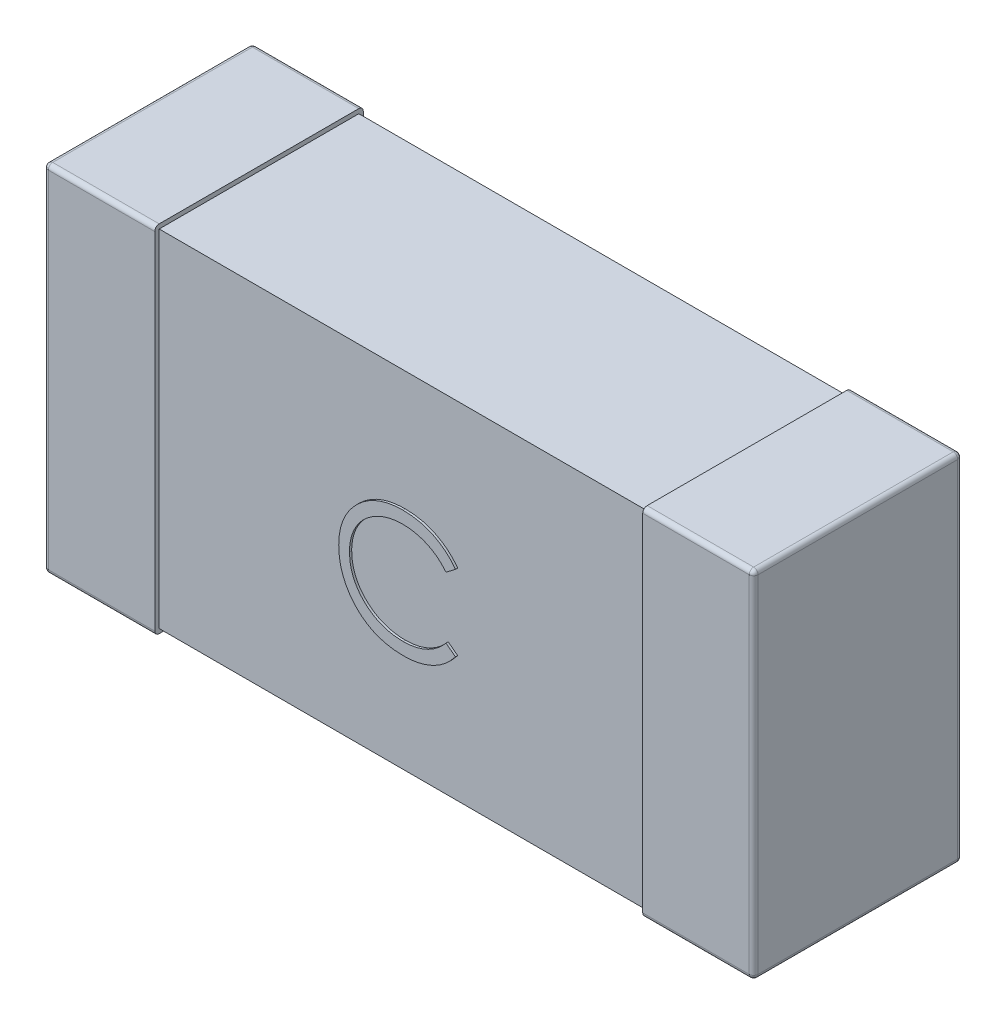
SolidWorks part; units mm, degrees
ref_plane "前视基准面" through (0, 0, 0) normal (0, 0, 1) x (1, 0, 0)
ref_plane "上视基准面" through (0, 0, 0) normal (0, 1, 0) x (1, 0, 0)
ref_plane "右视基准面" through (0, 0, 0) normal (1, 0, 0) x (0, 0, -1)
sketch "草图3" plane through (0, 0, 0) normal (0, 0, 1) x (1, 0, 0)
  line L0 (0, 0.9202) -> (0, -0.6542) construction
  line L1 (-1.6, 0.8) -> (-1.1, 0.8)
  line L2 (-1.6, 0.8) -> (-1.6, -0.8)
  line L3 (-1.6, -0.8) -> (-1.1, -0.8)
  line L4 (-1.1, 0.8) -> (-1.1, -0.8)
  line L5 (-1.6, 0.8) -> (-1.1, -0.8) construction
  line L6 (-1.6, -0.8) -> (-1.1, 0.8) construction
  line L7 (1.6, -0.8) -> (1.1, 0.8) construction
  line L8 (1.6, 0.8) -> (1.1, -0.8) construction
  line L9 (1.1, 0.8) -> (1.1, -0.8)
  line L10 (1.6, -0.8) -> (1.1, -0.8)
  line L11 (1.6, 0.8) -> (1.6, -0.8)
  line L12 (1.6, 0.8) -> (1.1, 0.8)
  point P0 (-1.35, 0)
  point P12 (1.35, 0)
  dimension "D1" = 0.5
  dimension "D2" = 1.6
  dimension "D3" = 1.6
extrude "凸台-拉伸1" add sketch "草图3" along normal blind 0.92 and the other way blind 0.02
sketch "草图5" plane through (0, 0, 0) normal (1, 0, 0) x (0, 0, -1)
  line L0 (0, 0.78) -> (0, -0.78)
  line L1 (0, -0.78) -> (-0.9, -0.78)
  line L2 (-0.9, -0.78) -> (-0.9, 0.78)
  line L3 (-0.9, 0.78) -> (0, 0.78)
  dimension "D1" = 1.56
  dimension "D2" = 0.9
extrude "凸台-拉伸3" add sketch "草图5" along normal mid plane 2.22
fillet "圆角3" radius 0.02 16 edges at (1.6, 0, -0.02) (1.6, -0.8, 0.45) (1.6, 0, 0.92) (1.6, 0.8, 0.45) (-1.6, 0, -0.02) (-1.6, 0.8, 0.45) (-1.6, 0, 0.92) (-1.6, -0.8, 0.45) (1.35, 0.8, -0.02) (1.35, -0.8, -0.02) (1.35, -0.8, 0.92) (1.35, 0.8, 0.92) (-1.35, -0.8, -0.02) (-1.35, -0.8, 0.92) (-1.35, 0.8, -0.02) (-1.35, 0.8, 0.92)
sketch "草图6" plane through (0, 0, 0.9) normal (0, 0, 1) x (1, 0, 0)
  text T0 "C" font "Century Gothic" height 0.54
extrude "凸台-拉伸4" add sketch "草图6" along normal blind 0.01
